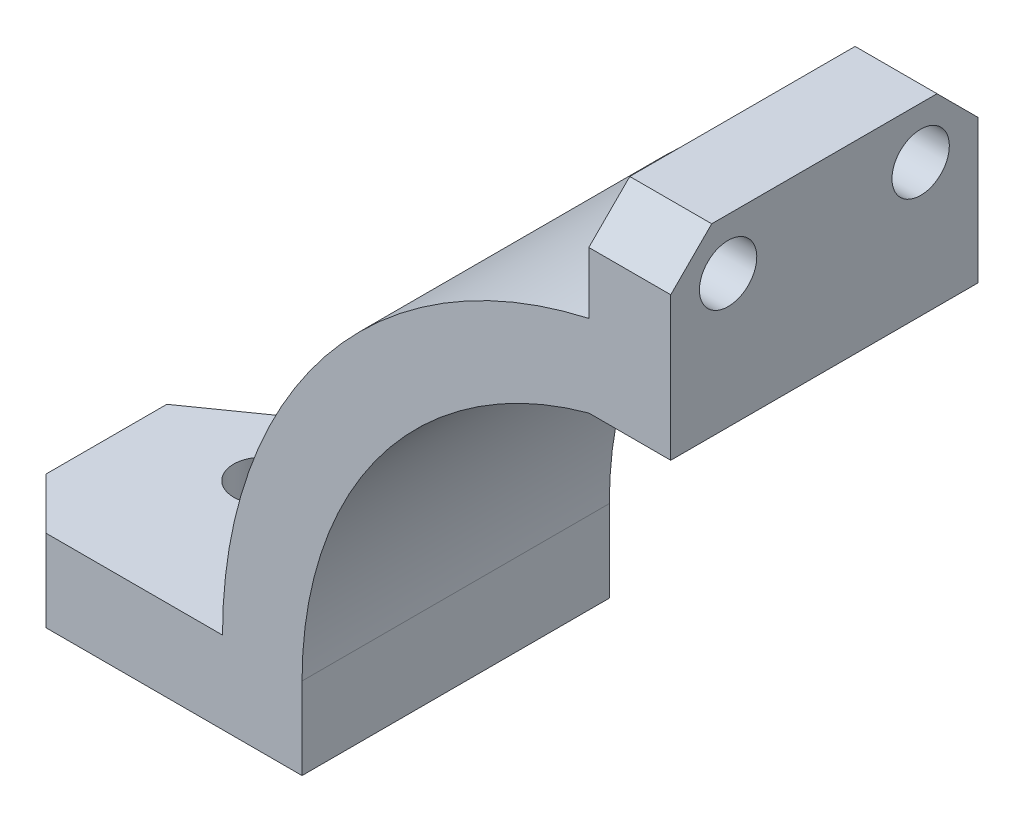
SolidWorks part; units mm, degrees
ref_plane "Front Plane" through (0, 0, 0) normal (0, 0, 1) x (1, 0, 0)
ref_plane "Top Plane" through (0, 0, 0) normal (0, 1, 0) x (1, 0, 0)
ref_plane "Right Plane" through (0, 0, 0) normal (1, 0, 0) x (0, 0, -1)
sketch "Sketch1" plane through (0, 0, 0) normal (0, 0, 1) x (1, 0, 0)
  line L0 (0, 0) -> (0, 50000) construction
  line L2 (-19, 0) -> (-19, -4)
  line L3 (-19, -4) -> (-34, -4)
  line L4 (-34, -4) -> (-34, 0)
  line L5 (-34, 0) -> (-22.8832, 0)
  line L6 (-5, 22.3303) -> (-5, 27.3303)
  line L7 (-5, 27.3303) -> (-1, 27.3303)
  line L8 (-1, 27.3303) -> (-1, 18.3303)
  line L9 (-1, 18.3303) -> (-5, 18.3303)
  arc A0 (-19, 0) -> (-5, 18.3303) centre (0, 0) cw
  arc A1 (-22.8832, 0) -> (-5, 22.3303) centre (0, 0) cw
  dimension "D2" = 19
  dimension "D1" = 4
  dimension "D3" = 15
  dimension "D4" = 4
  dimension "D5" = 4
  dimension "D6" = 9
  dimension "D7" = 1
extrude "Boss-Extrude1" add sketch "Sketch1" along normal blind 15
chamfer "Chamfer1" distance 2.5 2 edges at (-34, -2, 0) (-34, -2, 15)
sketch "Sketch2" plane through (-5, 0, 0) normal (-1, 0, 0) x (0, 0, 1)
  line L0 (15, 27.3303) -> (15, 22.3303) construction
  line L1 (0, 27.3303) -> (0, 22.3303) construction
  circle A0 centre (2.8, 24.8303) radius 1.4
  circle A1 centre (12.2, 24.8303) radius 1.4
  point P8 (0, 24.8303)
  dimension "D1" = 2.8
  dimension "D2" = 2.8
  dimension "D3" = 2.8
extrude "Cut-Extrude1" cut sketch "Sketch2" against normal blind 15
chamfer "Chamfer2" distance 2 angle 45 2 edges at (-3, 27.3303, 15) (-3, 27.3303, 0)
sketch "Sketch3" plane through (0, 0, 0) normal (0, 1, 0) x (1, 0, 0)
  line L0 (-34, -12.5) -> (-34, -2.5) construction
  line L2 (-22.8832, 0) -> (-34, 0.1) construction
  line L3 (45.4373, 0.1) -> (-44.4791, 0.1) construction
  circle A0 centre (-28.4416, -7.5) radius 1.4
  point P2 (-28.4416, 0.05)
  point P5 (-34, -7.5)
  dimension "D1" = 2.8
extrude "Cut-Extrude2" cut sketch "Sketch3" against normal through all contours A0
sketch "Sketch4" plane through (0, -4, 0) normal (0, -1, 0) x (1, 0, 0)
  line L0 (-24.6361, 0) -> (-34, 6.6004)
  line L1 (-31.5, 0) -> (-19, 0) construction
  line L2 (-34, 12.5) -> (-34, 2.5) construction
  line L3 (-34, 6.6004) -> (-34, 2.5)
  line L4 (-34, 2.5) -> (-31.5, 0)
  line L5 (-34, 2.5) -> (-31.5, 0) construction
  line L6 (-31.5, 0) -> (-24.6361, 0)
extrude "Cut-Extrude3" cut sketch "Sketch4" against normal blind 25 contours L6 L0 L3 L4
